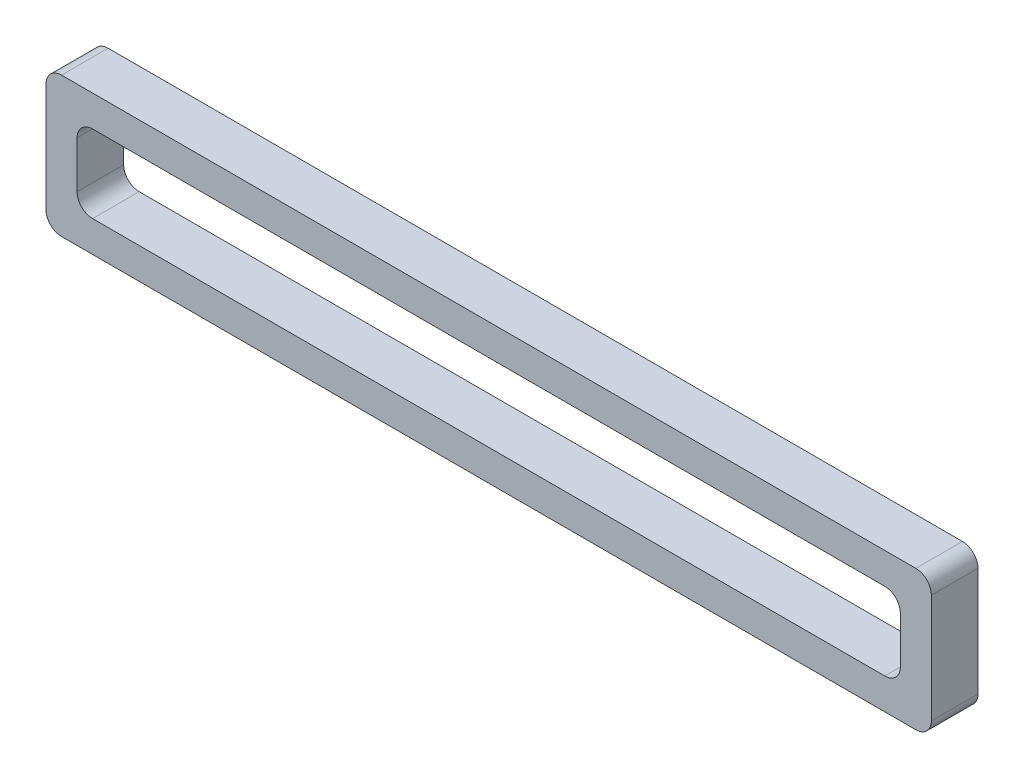
SolidWorks part; units mm, degrees
ref_plane "Front Plane" through (0, 0, 0) normal (0, 0, 1) x (1, 0, 0)
ref_plane "Top Plane" through (0, 0, 0) normal (0, 1, 0) x (1, 0, 0)
ref_plane "Right Plane" through (0, 0, 0) normal (1, 0, 0) x (0, 0, -1)
sketch "Sketch1" plane through (0, 0, 0) normal (0, 0, 1) x (1, 0, 0)
  line L1 (-25.5, 2.5) -> (25.5, 2.5)
  line L2 (-26.5, 1.5) -> (-26.5, -1.5)
  line L3 (-25.5, -2.5) -> (25.5, -2.5)
  line L4 (26.5, 1.5) -> (26.5, -1.5)
  line L5 (-26.5, 2.5) -> (26.5, -2.5) construction
  line L6 (-26.5, -2.5) -> (26.5, 2.5) construction
  line L7 (-27.5, 4.5) -> (27.5, 4.5)
  line L8 (-28.5, 3.5) -> (-28.5, -3.5)
  line L9 (-27.5, -4.5) -> (27.5, -4.5)
  line L10 (28.5, 3.5) -> (28.5, -3.5)
  line L11 (-28.5, 4.5) -> (28.5, -4.5) construction
  line L12 (-28.5, -4.5) -> (28.5, 4.5) construction
  arc A0 (27.5, -4.5) -> (28.5, -3.5) centre (27.5, -3.5) ccw
  arc A1 (-28.5, -3.5) -> (-27.5, -4.5) centre (-27.5, -3.5) ccw
  arc A2 (-27.5, 4.5) -> (-28.5, 3.5) centre (-27.5, 3.5) ccw
  arc A3 (27.5, 4.5) -> (28.5, 3.5) centre (27.5, 3.5) cw
  arc A4 (25.5, 2.5) -> (26.5, 1.5) centre (25.5, 1.5) cw
  arc A5 (25.5, -2.5) -> (26.5, -1.5) centre (25.5, -1.5) ccw
  arc A6 (-26.5, -1.5) -> (-25.5, -2.5) centre (-25.5, -1.5) ccw
  arc A7 (-25.5, 2.5) -> (-26.5, 1.5) centre (-25.5, 1.5) ccw
  point P0 (0, 0)
  point P6 (0, 0)
  dimension "D1" = 1
  dimension "D2" = 51
  dimension "D3" = 2
  dimension "D4" = 2
  dimension "D5" = 3
extrude "Boss-Extrude1" add sketch "Sketch1" along normal blind 3
